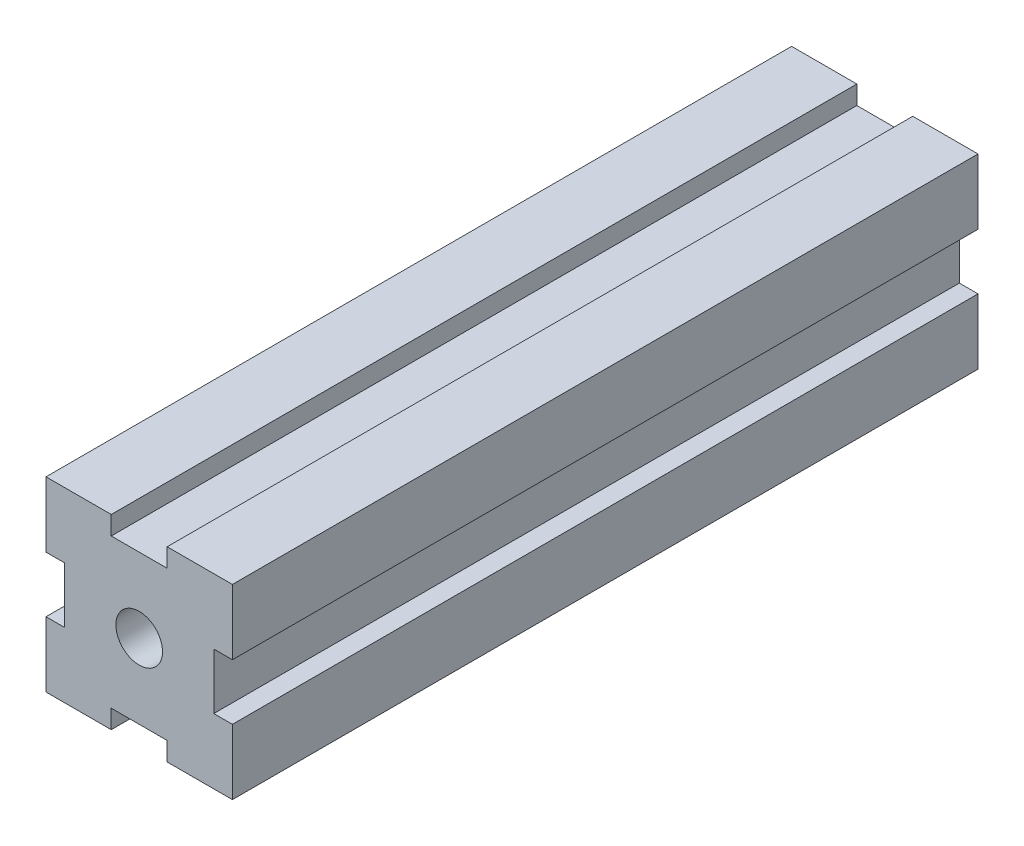
SolidWorks part; units mm, degrees
ref_plane "前视基准面" through (0, 0, 0) normal (0, 0, 1) x (1, 0, 0)
ref_plane "上视基准面" through (0, 0, 0) normal (0, 1, 0) x (1, 0, 0)
ref_plane "右视基准面" through (0, 0, 0) normal (1, 0, 0) x (0, 0, -1)
sketch "草图1" plane through (0, 0, 0) normal (0, 0, 1) x (1, 0, 0)
  line L0 (0, -13) -> (0, -20)
  line L1 (0, 0) -> (7, 0)
  line L2 (0, 0) -> (0, -7)
  line L3 (0, -20) -> (7, -20)
  line L4 (20, 0) -> (20, -7)
  line L5 (20, -7) -> (18, -7)
  line L6 (13, -20) -> (20, -20)
  line L7 (20, -13) -> (18, -13)
  line L8 (18, -7) -> (18, -13)
  line L9 (0, -7) -> (2, -7)
  line L10 (13, 0) -> (20, 0)
  line L11 (0, -13) -> (2, -13)
  line L12 (2, -7) -> (2, -13)
  line L13 (20, -13) -> (20, -20)
  line L14 (7, 0) -> (7, -2)
  line L15 (7, -2) -> (13, -2)
  line L16 (13, 0) -> (13, -2)
  line L17 (0, -7) -> (0, -13) construction
  line L18 (7, -20) -> (7, -18)
  line L19 (7, -18) -> (13, -18)
  line L20 (13, -20) -> (13, -18)
  line L21 (7, 0) -> (13, 0) construction
  line L22 (20, -7) -> (20, -13) construction
  line L23 (13, -20) -> (7, -20) construction
  line L24 (2, -10) -> (18, -10) construction
  line L25 (10, -2) -> (10, -18) construction
  circle A0 centre (10, -10) radius 2.5
  point P21 (10, 0)
  point P22 (10, -2)
  point P23 (10, -18)
  point P24 (2, -10)
  point P25 (18, -10)
  point P26 (0, -10)
  dimension "D13" = 5
  dimension "D1" = 20
  dimension "D2" = 20
  dimension "D3" = 6
  dimension "D4" = 6
  dimension "D5" = 6
  dimension "D6" = 6
  dimension "D7" = 10
  dimension "D8" = 10
  dimension "D9" = 2
  dimension "D10" = 2
  dimension "D11" = 2
  dimension "D12" = 2
extrude "凸台-拉伸1" add sketch "草图1" along normal blind 80
